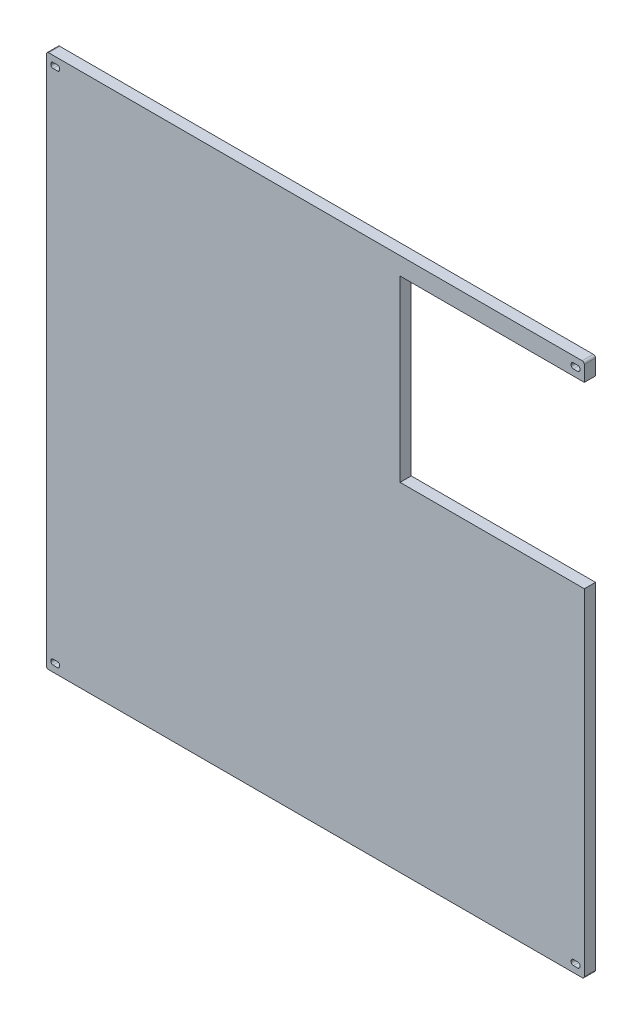
SolidWorks part; units mm, degrees
ref_plane "Front Plane" through (0, 0, 0) normal (0, 0, 1) x (1, 0, 0)
ref_plane "Top Plane" through (0, 0, 0) normal (0, 1, 0) x (1, 0, 0)
ref_plane "Right Plane" through (0, 0, 0) normal (1, 0, 0) x (0, 0, -1)
sketch "Sketch1" plane through (0, 0, 0) normal (0, 0, 1) x (1, 0, 0)
  line L0 (-5, 10.5) -> (-5, 9.5)
  line L1 (0, 0) -> (-611.632, 0)
  line L2 (0, 0) -> (0, 384.2809)
  line L3 (0, 607.568) -> (-611.632, 607.568)
  line L4 (-611.632, 0) -> (-611.632, 607.568)
  line L5 (0, 587.4809) -> (0, 607.568)
  line L6 (0, 587.4809) -> (-209.55, 587.4809)
  line L8 (0, 384.2809) -> (-209.55, 384.2809)
  line L9 (-209.55, 587.4809) -> (-209.55, 384.2809)
  line L10 (-7.5, 13) -> (-12.5, 13)
  line L11 (-15, 10.5) -> (-15, 9.5)
  line L12 (-7.5, 7) -> (-12.5, 7)
  line L13 (-10, 13) -> (-10, 7) construction
  line L14 (-15, 10) -> (-5, 10) construction
  line L15 (-596.63, 10.5) -> (-596.63, 9.5)
  line L16 (-599.13, 7) -> (-604.13, 7)
  line L17 (-606.63, 10.5) -> (-606.63, 9.5)
  line L18 (-599.13, 13) -> (-604.13, 13)
  line L19 (-596.63, 598.07) -> (-596.63, 597.07)
  line L20 (-599.13, 594.57) -> (-604.13, 594.57)
  line L21 (-606.63, 598.07) -> (-606.63, 597.07)
  line L22 (-599.13, 600.57) -> (-604.13, 600.57)
  line L23 (-5, 598.07) -> (-5, 597.07)
  line L24 (-7.5, 594.57) -> (-12.5, 594.57)
  line L25 (-15, 598.07) -> (-15, 597.07)
  line L26 (-7.5, 600.57) -> (-12.5, 600.57)
  arc A0 (-5, 10.5) -> (-7.5, 13) centre (-7.5, 10.5) ccw
  arc A1 (-12.5, 13) -> (-15, 10.5) centre (-12.5, 10.5) ccw
  arc A2 (-5, 9.5) -> (-7.5, 7) centre (-7.5, 9.5) cw
  arc A3 (-15, 9.5) -> (-12.5, 7) centre (-12.5, 9.5) ccw
  arc A4 (-596.63, 9.5) -> (-599.13, 7) centre (-599.13, 9.5) cw
  arc A5 (-606.63, 9.5) -> (-604.13, 7) centre (-604.13, 9.5) ccw
  arc A6 (-604.13, 13) -> (-606.63, 10.5) centre (-604.13, 10.5) ccw
  arc A7 (-596.63, 10.5) -> (-599.13, 13) centre (-599.13, 10.5) ccw
  arc A8 (-596.63, 597.07) -> (-599.13, 594.57) centre (-599.13, 597.07) cw
  arc A9 (-606.63, 597.07) -> (-604.13, 594.57) centre (-604.13, 597.07) ccw
  arc A10 (-604.13, 600.57) -> (-606.63, 598.07) centre (-604.13, 598.07) ccw
  arc A11 (-596.63, 598.07) -> (-599.13, 600.57) centre (-599.13, 598.07) ccw
  arc A12 (-5, 597.07) -> (-7.5, 594.57) centre (-7.5, 597.07) cw
  arc A13 (-15, 597.07) -> (-12.5, 594.57) centre (-12.5, 597.07) ccw
  arc A14 (-12.5, 600.57) -> (-15, 598.07) centre (-12.5, 598.07) ccw
  arc A15 (-5, 598.07) -> (-7.5, 600.57) centre (-7.5, 598.07) ccw
  dimension "D4" = 2.5
  dimension "D1" = 611.632
  dimension "D2" = 607.568
  dimension "D3" = 6
  dimension "D5" = 10
  dimension "D6" = 10
  dimension "D7" = 2
  dimension "D8" = 2
  dimension "1000" = 10
  dimension "D9" = 5
  dimension "D10" = 6.998
  dimension "D11" = 5.002
  dimension "D12" = 384.2809
  dimension "D13" = 203.2
  dimension "D14" = 209.55
extrude "Boss-Extrude2" add sketch "Sketch1" along normal blind 12.7
fillet "Fillet2" radius 2.5 4 edges at (-611.632, 0, 6.35) (0, 0, 6.35) (-611.632, 607.568, 6.35) (0, 607.568, 6.35)
